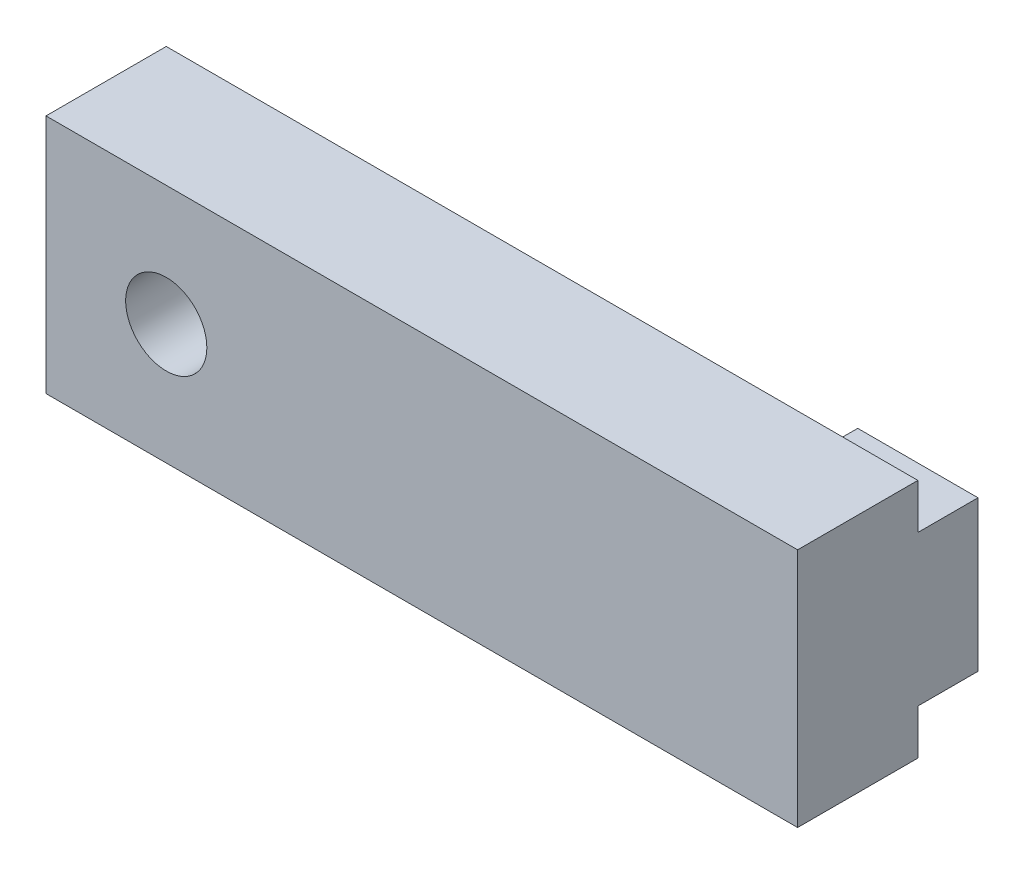
SolidWorks part; units mm, degrees
ref_plane "Front Plane" through (0, 0, 0) normal (0, 0, 1) x (1, 0, 0)
ref_plane "Top Plane" through (0, 0, 0) normal (0, 1, 0) x (1, 0, 0)
ref_plane "Right Plane" through (0, 0, 0) normal (1, 0, 0) x (0, 0, -1)
other "Configuration Table"
sketch "Sketch2" plane through (0, 0, 0) normal (0, 0, 1) x (1, 0, 0)
  line L1 (-8, -8) -> (42, -8)
  line L2 (-8, -8) -> (-8, 8)
  line L3 (-8, 8) -> (42, 8)
  line L4 (42, -8) -> (42, 8)
extrude "Clamp_arm" add sketch "Sketch2" along normal blind 8 from offset 0
sketch "Sketch3" plane through (0, 0, 0) normal (0, 0, 1) x (1, 0, 0)
  circle A0 centre (0, 0) radius 2.7
extrude "Pivot_bolt_clearance" cut sketch "Sketch3" along normal blind 8 from offset 0
sketch "Sketch4" plane through (0, 0, 0) normal (0, 0, 1) x (1, 0, 0)
  line L0 (42, -8) -> (42, 8) construction
  line L1 (34, -5) -> (42, -5)
  line L2 (34, -5) -> (34, 5)
  line L3 (34, 5) -> (42, 5)
  line L4 (42, -5) -> (42, 5)
extrude "Contact_nose" add sketch "Sketch4" along normal blind 4 from offset 4
